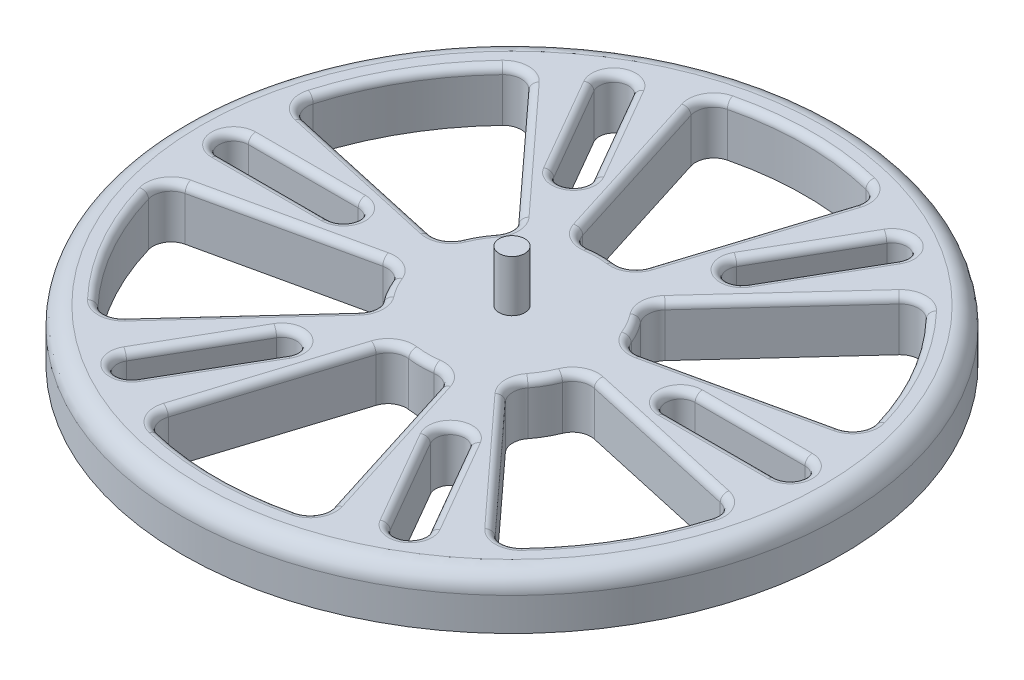
SolidWorks part; units mm, degrees
ref_plane "Plan de face" through (0, 0, 0) normal (0, 0, 1) x (1, 0, 0)
ref_plane "Plan de dessus" through (0, 0, 0) normal (0, 1, 0) x (1, 0, 0)
ref_plane "Plan de droite" through (0, 0, 0) normal (1, 0, 0) x (0, 0, -1)
sketch "Esquisse1" plane through (0, 0, 0) normal (0, 1, 0) x (1, 0, 0)
  line L0 (0, 45) -> (0, -45) construction
  line L1 (-13.5318, 42.9173) -> (0, 0) construction
  line L2 (13.5318, 42.9173) -> (0, 0) construction
  line L3 (-11.2514, 35.6848) -> (-4.4475, 14.1057)
  line L4 (4.4475, 14.1057) -> (11.2514, 35.6848)
  line L15 (14.4396, 3.2012) -> (36.5297, 8.0984)
  line L16 (25.2783, 27.5864) -> (9.9921, 10.9045)
  line L17 (9.9921, -10.9045) -> (25.2783, -27.5864)
  line L18 (36.5297, -8.0984) -> (14.4396, -3.2012)
  line L19 (-4.4475, -14.1057) -> (-11.2514, -35.6848)
  line L20 (11.2514, -35.6848) -> (4.4475, -14.1057)
  line L21 (-14.4396, -3.2012) -> (-36.5297, -8.0984)
  line L22 (-25.2783, -27.5864) -> (-9.9921, -10.9045)
  line L23 (-9.9921, 10.9045) -> (-25.2783, 27.5864)
  line L24 (-36.5297, 8.0984) -> (-14.4396, 3.2012)
  line L25 (0, 0) -> (22.5, 38.9711) construction
  line L26 (11.5, 19.9186) -> (19, 32.909) construction
  line L27 (9.7679, 20.9186) -> (17.2679, 33.909)
  line L28 (13.2321, 18.9186) -> (20.7321, 31.909)
  line L29 (23, 0) -> (38, 0) construction
  line L30 (23, 2) -> (38, 2)
  line L31 (23, -2) -> (38, -2)
  line L32 (11.5, -19.9186) -> (19, -32.909) construction
  line L33 (13.2321, -18.9186) -> (20.7321, -31.909)
  line L34 (9.7679, -20.9186) -> (17.2679, -33.909)
  line L35 (-11.5, -19.9186) -> (-19, -32.909) construction
  line L36 (-9.7679, -20.9186) -> (-17.2679, -33.909)
  line L37 (-13.2321, -18.9186) -> (-20.7321, -31.909)
  line L38 (-23, 0) -> (-38, 0) construction
  line L39 (-23, -2) -> (-38, -2)
  line L40 (-23, 2) -> (-38, 2)
  line L41 (-11.5, 19.9186) -> (-19, 32.909) construction
  line L42 (-13.2321, 18.9186) -> (-20.7321, 31.909)
  line L43 (-9.7679, 20.9186) -> (-17.2679, 33.909)
  circle A0 centre (0, 0) radius 45
  arc A1 (-9.4582, 38.8657) -> (9.4582, 38.8657) centre (0, 0) cw
  arc A2 (-1.7193, 12.3812) -> (1.7193, 12.3812) centre (0, 0) cw
  arc A3 (9.4582, 38.8657) -> (11.2514, 35.6848) centre (8.8671, 36.4366) cw
  arc A4 (1.7193, 12.3812) -> (4.4475, 14.1057) centre (2.0632, 14.8574) ccw
  arc A5 (-1.7193, 12.3812) -> (-4.4475, 14.1057) centre (-2.0632, 14.8574) cw
  arc A6 (-9.4582, 38.8657) -> (-11.2514, 35.6848) centre (-8.8671, 36.4366) ccw
  arc A37 (11.5821, 4.7016) -> (14.4396, 3.2012) centre (13.8985, 5.6419) ccw
  arc A38 (38.3878, 11.2418) -> (36.5297, 8.0984) centre (35.9886, 10.5392) cw
  arc A39 (28.9296, 27.6239) -> (38.3878, 11.2418) centre (0, 0) cw
  arc A40 (28.9296, 27.6239) -> (25.2783, 27.5864) centre (27.1215, 25.8974) ccw
  arc A41 (9.8628, 7.6796) -> (9.9921, 10.9045) centre (11.8353, 9.2155) cw
  arc A42 (9.8628, 7.6796) -> (11.5821, 4.7016) centre (0, 0) cw
  arc A43 (9.8628, -7.6796) -> (9.9921, -10.9045) centre (11.8353, -9.2155) ccw
  arc A44 (28.9296, -27.6239) -> (25.2783, -27.5864) centre (27.1215, -25.8974) cw
  arc A45 (38.3878, -11.2418) -> (28.9296, -27.6239) centre (0, 0) cw
  arc A46 (38.3878, -11.2418) -> (36.5297, -8.0984) centre (35.9886, -10.5392) ccw
  arc A47 (11.5821, -4.7016) -> (14.4396, -3.2012) centre (13.8985, -5.6419) cw
  arc A48 (11.5821, -4.7016) -> (9.8628, -7.6796) centre (0, 0) cw
  arc A49 (-1.7193, -12.3812) -> (-4.4475, -14.1057) centre (-2.0632, -14.8574) ccw
  arc A50 (-9.4582, -38.8657) -> (-11.2514, -35.6848) centre (-8.8671, -36.4366) cw
  arc A51 (9.4582, -38.8657) -> (-9.4582, -38.8657) centre (0, 0) cw
  arc A52 (9.4582, -38.8657) -> (11.2514, -35.6848) centre (8.8671, -36.4366) ccw
  arc A53 (1.7193, -12.3812) -> (4.4475, -14.1057) centre (2.0632, -14.8574) cw
  arc A54 (1.7193, -12.3812) -> (-1.7193, -12.3812) centre (0, 0) cw
  arc A55 (-11.5821, -4.7016) -> (-14.4396, -3.2012) centre (-13.8985, -5.6419) ccw
  arc A56 (-38.3878, -11.2418) -> (-36.5297, -8.0984) centre (-35.9886, -10.5392) cw
  arc A57 (-28.9296, -27.6239) -> (-38.3878, -11.2418) centre (0, 0) cw
  arc A58 (-28.9296, -27.6239) -> (-25.2783, -27.5864) centre (-27.1215, -25.8974) ccw
  arc A59 (-9.8628, -7.6796) -> (-9.9921, -10.9045) centre (-11.8353, -9.2155) cw
  arc A60 (-9.8628, -7.6796) -> (-11.5821, -4.7016) centre (0, 0) cw
  arc A61 (-9.8628, 7.6796) -> (-9.9921, 10.9045) centre (-11.8353, 9.2155) ccw
  arc A62 (-28.9296, 27.6239) -> (-25.2783, 27.5864) centre (-27.1215, 25.8974) cw
  arc A63 (-38.3878, 11.2418) -> (-28.9296, 27.6239) centre (0, 0) cw
  arc A64 (-38.3878, 11.2418) -> (-36.5297, 8.0984) centre (-35.9886, 10.5392) ccw
  arc A65 (-11.5821, 4.7016) -> (-14.4396, 3.2012) centre (-13.8985, 5.6419) cw
  arc A66 (-11.5821, 4.7016) -> (-9.8628, 7.6796) centre (0, 0) cw
  arc A67 (9.7679, 20.9186) -> (13.2321, 18.9186) centre (11.5, 19.9186) ccw
  arc A68 (20.7321, 31.909) -> (17.2679, 33.909) centre (19, 32.909) ccw
  circle A69 centre (0, 0) radius 40 construction
  arc A70 (23, 2) -> (23, -2) centre (23, 0) ccw
  arc A71 (38, -2) -> (38, 2) centre (38, 0) ccw
  arc A72 (13.2321, -18.9186) -> (9.7679, -20.9186) centre (11.5, -19.9186) ccw
  arc A73 (17.2679, -33.909) -> (20.7321, -31.909) centre (19, -32.909) ccw
  arc A74 (-9.7679, -20.9186) -> (-13.2321, -18.9186) centre (-11.5, -19.9186) ccw
  arc A75 (-20.7321, -31.909) -> (-17.2679, -33.909) centre (-19, -32.909) ccw
  arc A76 (-23, -2) -> (-23, 2) centre (-23, 0) ccw
  arc A77 (-38, 2) -> (-38, -2) centre (-38, 0) ccw
  arc A78 (-13.2321, 18.9186) -> (-9.7679, 20.9186) centre (-11.5, 19.9186) ccw
  arc A79 (-17.2679, 33.909) -> (-20.7321, 31.909) centre (-19, 32.909) ccw
  point P14 (12.0282, 38.1487)
  point P17 (3.7588, 11.9215)
  point P20 (-3.7588, 11.9215)
  point P23 (-12.0282, 38.1487)
  point P85 (0, 0)
  point P87 (15.25, 26.4138)
  point P93 (0, 0)
  point P94 (0, 0)
  point P98 (30.5, 0)
  point P105 (15.25, -26.4138)
  point P112 (-15.25, -26.4138)
  point P119 (-30.5, 0)
  point P126 (-15.25, 26.4138)
  point P131 (0, 0)
  dimension "D1" = 90
  dimension "D3" = 27.5
  dimension "D5" = 2.5
  dimension "D11" = 7
  dimension "D2" = 35
  dimension "D4" = 5
  dimension "D7" = 30
  dimension "D8" = 15
  dimension "D9" = 4
  dimension "D10" = 6
  dimension "D6" = 6
extrude "Boss.-Extru.1" add sketch "Esquisse1" along normal blind 7
sketch "Esquisse2" plane through (0, 7, 0) normal (0, 1, 0) x (1, 0, 0)
  circle A0 centre (0, 0) radius 1.75
  circle A1 centre (0, 0) radius 45
  circle A2 centre (0, 0) radius 45
  dimension "D2" = 3.5
  dimension "D1" = 0
extrude "Boss.-Extru.2" add sketch "Esquisse2" along normal blind 7 contours A0
fillet "Congé1" radius 2.5 1 edges at (0, 7, 45)
fillet "Congé2" radius 1 72 edges at (27.0958, 7, -28.3973) (34.641, 7, -20) (38.1407, 7, -9.267) (25.4846, 7, -5.6498) (12.7363, 7, -3.4285) (10.8253, 7, -6.25) (9.3373, 7, -9.3157) (40, 7, 0) (30.5, 7, 2) (21, 7, 0) (38.1407, 7, 9.267) (34.641, 7, 20) (27.0958, 7, 28.3973) (17.6352, 7, 19.2454) (9.3373, 7, 9.3157) (10.8253, 7, 6.25) (12.7363, 7, 3.4285) (16.9821, 7, 25.4138) (20, 7, 34.641) (13.5179, 7, 27.4138) (-3.399, 7, 12.7442) (0, 7, 12.5) (3.399, 7, 12.7442) (7.8494, 7, 24.8952) (11.0449, 7, 37.6643) (0, 7, 40) (-11.0449, 7, 37.6643) (-10.5, 7, 18.1865) (-13.5179, 7, 27.4138) (-20, 7, 34.641) (-12.7363, 7, 3.4285) (-10.8253, 7, 6.25) (-9.3373, 7, 9.3157) (-17.6352, 7, 19.2454) (-27.0958, 7, 28.3973) (-34.641, 7, 20) (-38.1407, 7, 9.267) (-21, 7, 0) (-30.5, 7, 2) (-40, 7, 0) (-10.5, 7, -18.1865) (-16.9821, 7, -25.4138) (-20, 7, -34.641) (20, 7, -34.641) (16.9821, 7, -25.4138) (10.5, 7, -18.1865) (-9.3373, 7, -9.3157) (-10.8253, 7, -6.25) (-12.7363, 7, -3.4285) (-25.4846, 7, -5.6498) (-38.1407, 7, -9.267) (-34.641, 7, -20) (-27.0958, 7, -28.3973) (-11.0449, 7, -37.6643) (0, 7, -40) (11.0449, 7, -37.6643) (7.8494, 7, -24.8952) (3.399, 7, -12.7442) (0, 7, -12.5) (-3.399, 7, -12.7442) (17.6352, 7, -19.2454) (30.5, 7, -2) (25.4846, 7, 5.6498) (10.5, 7, 18.1865) (-7.8494, 7, 24.8952) (-16.9821, 7, 25.4138) (-25.4846, 7, 5.6498) (-30.5, 7, -2) (-13.5179, 7, -27.4138) (13.5179, 7, -27.4138) (-17.6352, 7, -19.2454) (-7.8494, 7, -24.8952)
